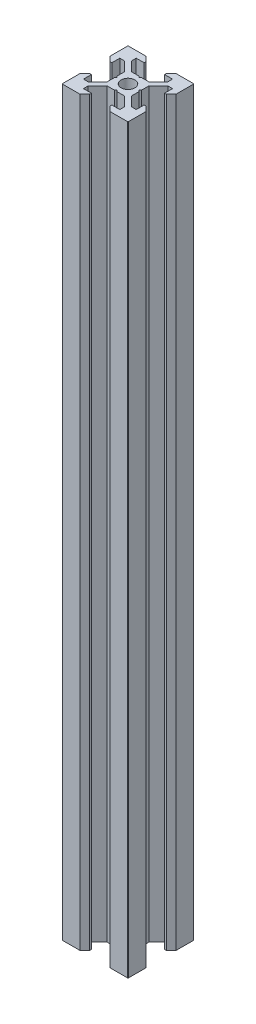
SolidWorks part; units mm, degrees
ref_plane "Plan de face" through (0, 0, 0) normal (0, 0, 1) x (1, 0, 0)
ref_plane "Plan de dessus" through (0, 0, 0) normal (0, 1, 0) x (1, 0, 0)
ref_plane "Plan de droite" through (0, 0, 0) normal (1, 0, 0) x (0, 0, -1)
sketch "Esquisse1" plane through (0, 0, 0) normal (0, 1, 0) x (1, 0, 0)
  line L0 (0, -68.4) -> (0, 76.1968) construction
  line L1 (-68.4, 0) -> (76.1968, 0) construction
  line L2 (0, 0) -> (13.0871, 13.0871) construction
  line L4 (3.7, 2.6393) -> (6.5607, 5.5)
  line L5 (6.5607, 5.5) -> (8, 5.5)
  line L6 (8, 5.5) -> (8, 3.1)
  line L7 (8, 3.1) -> (8.52, 3.1)
  line L8 (8.52, 3.1) -> (10, 4.58)
  line L9 (10, 4.58) -> (10, 9.82)
  line L10 (0.3536, 3.7) -> (0, 3.3464)
  line L60 (3.7, 2.6393) -> (3.7, 0.3536)
  line L61 (3.7, 0.3536) -> (3.3464, 0)
  line L62 (2.6393, 3.7) -> (0.3536, 3.7)
  line L63 (4.58, 10) -> (9.82, 10)
  line L64 (3.1, 8.52) -> (4.58, 10)
  line L65 (3.1, 8) -> (3.1, 8.52)
  line L66 (5.5, 8) -> (3.1, 8)
  line L67 (5.5, 6.5607) -> (5.5, 8)
  line L68 (2.6393, 3.7) -> (5.5, 6.5607)
  line L69 (2.6393, -3.7) -> (5.5, -6.5607)
  line L70 (5.5, -6.5607) -> (5.5, -8)
  line L71 (5.5, -8) -> (3.1, -8)
  line L72 (3.1, -8) -> (3.1, -8.52)
  line L73 (3.1, -8.52) -> (4.58, -10)
  line L74 (4.58, -10) -> (9.82, -10)
  line L75 (3.7, -0.3536) -> (3.3464, 0)
  line L76 (2.6393, -3.7) -> (0.3536, -3.7)
  line L77 (0.3536, -3.7) -> (0, -3.3464)
  line L78 (3.7, -2.6393) -> (3.7, -0.3536)
  line L79 (10, -4.58) -> (10, -9.82)
  line L80 (8.52, -3.1) -> (10, -4.58)
  line L81 (8, -3.1) -> (8.52, -3.1)
  line L82 (8, -5.5) -> (8, -3.1)
  line L83 (6.5607, -5.5) -> (8, -5.5)
  line L84 (3.7, -2.6393) -> (6.5607, -5.5)
  line L85 (-3.7, -2.6393) -> (-6.5607, -5.5)
  line L86 (-6.5607, -5.5) -> (-8, -5.5)
  line L87 (-8, -5.5) -> (-8, -3.1)
  line L88 (-8, -3.1) -> (-8.52, -3.1)
  line L89 (-8.52, -3.1) -> (-10, -4.58)
  line L90 (-10, -4.58) -> (-10, -9.82)
  line L91 (-0.3536, -3.7) -> (0, -3.3464)
  line L92 (-3.7, -2.6393) -> (-3.7, -0.3536)
  line L93 (-3.7, -0.3536) -> (-3.3464, 0)
  line L94 (-2.6393, -3.7) -> (-0.3536, -3.7)
  line L95 (-4.58, -10) -> (-9.82, -10)
  line L96 (-3.1, -8.52) -> (-4.58, -10)
  line L97 (-3.1, -8) -> (-3.1, -8.52)
  line L98 (-5.5, -8) -> (-3.1, -8)
  line L99 (-5.5, -6.5607) -> (-5.5, -8)
  line L100 (-2.6393, -3.7) -> (-5.5, -6.5607)
  line L101 (-2.6393, 3.7) -> (-5.5, 6.5607)
  line L102 (-5.5, 6.5607) -> (-5.5, 8)
  line L103 (-5.5, 8) -> (-3.1, 8)
  line L104 (-3.1, 8) -> (-3.1, 8.52)
  line L105 (-3.1, 8.52) -> (-4.58, 10)
  line L106 (-4.58, 10) -> (-9.82, 10)
  line L107 (-3.7, 0.3536) -> (-3.3464, 0)
  line L108 (-2.6393, 3.7) -> (-0.3536, 3.7)
  line L109 (-0.3536, 3.7) -> (0, 3.3464)
  line L110 (-3.7, 2.6393) -> (-3.7, 0.3536)
  line L111 (-10, 4.58) -> (-10, 9.82)
  line L112 (-8.52, 3.1) -> (-10, 4.58)
  line L113 (-8, 3.1) -> (-8.52, 3.1)
  line L114 (-8, 5.5) -> (-8, 3.1)
  line L115 (-6.5607, 5.5) -> (-8, 5.5)
  line L116 (-3.7, 2.6393) -> (-6.5607, 5.5)
  circle A0 centre (0, 0) radius 2.1
  arc A1 (10, 9.82) -> (9.82, 10) centre (9.82, 9.82) ccw
  arc A2 (9.82, -10) -> (10, -9.82) centre (9.82, -9.82) ccw
  arc A3 (-10, -9.82) -> (-9.82, -10) centre (-9.82, -9.82) ccw
  arc A4 (-9.82, 10) -> (-10, 9.82) centre (-9.82, 9.82) ccw
  point P27 (10, 10)
  point P28 (10, 10)
  point P47 (10, -10)
  point P48 (0, 0)
  point P68 (-10, -10)
  point P69 (0, 0)
  point P74 (0, 0)
  point P92 (-10, 10)
  point P93 (0, 0)
  point P96 (0, 0)
  dimension "D9" = 4.2
  dimension "D11" = 4
  dimension "D10" = 0.18
  dimension "D1" = 45
  dimension "D2" = 4.3
  dimension "D3" = 10
  dimension "D4" = 0.75
  dimension "D5" = 3.1
  dimension "D6" = 5.5
  dimension "D7" = 4.58
  dimension "D8" = 2
  dimension "D12" = 0.5
extrude "Boss.-Extru.1" add sketch "Esquisse1" along normal blind 225
